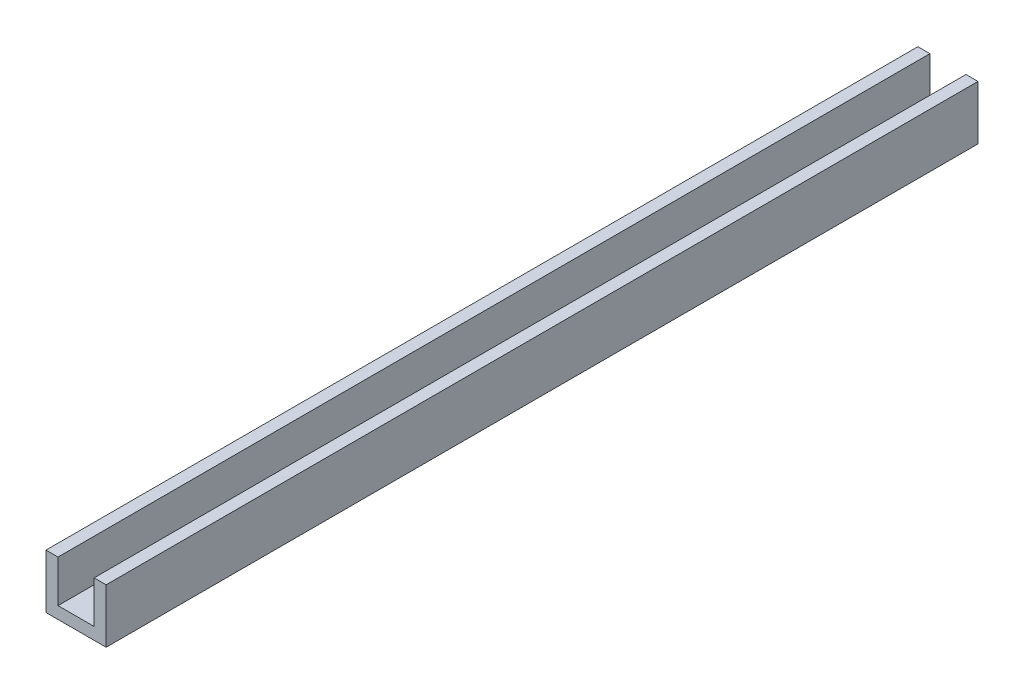
SolidWorks part; units mm, degrees
ref_plane "正面" through (0, 0, 0) normal (0, 0, 1) x (1, 0, 0)
ref_plane "平面" through (0, 0, 0) normal (0, 1, 0) x (1, 0, 0)
ref_plane "右側面" through (0, 0, 0) normal (1, 0, 0) x (0, 0, -1)
sketch "ｽｹｯﾁ1" plane through (0, 0, 0) normal (0, 0, 1) x (1, 0, 0)
  line L0 (-5, 9) -> (-5, 0)
  line L1 (-5, 0) -> (5, 0)
  line L2 (5, 0) -> (5, 9)
  line L3 (5, 9) -> (3, 9)
  line L4 (3, 9) -> (3, 2)
  line L5 (3, 2) -> (-3, 2)
  line L6 (-3, 2) -> (-3, 9)
  line L7 (-3, 9) -> (-5, 9)
  dimension "D1" = 9
  dimension "D2" = 9
  dimension "D3" = 10
  dimension "D4" = 5
  dimension "D5" = 2
  dimension "D6" = 2
  dimension "D7" = 2
extrude "ﾎﾞｽ - 押し出し1" add sketch "ｽｹｯﾁ1" along normal blind 245
sketch "ｽｹｯﾁ2" plane through (0, 0, 0) normal (0, -1, 0) x (1, 0, 0)
  line L0 (-5, 245) -> (5, 245) construction
  circle A0 centre (0, 225) radius 2.5
  circle A1 centre (0, 217) radius 2.5
  circle A2 centre (0, 122.5) radius 2.5
  circle A3 centre (0, 209) radius 2.5
  circle A4 centre (0, 193) radius 2.5
  circle A5 centre (0, 161) radius 2.5
  dimension "D1" = 20
  dimension "D3" = 5
  dimension "D4" = 5
  dimension "D5" = 5
  dimension "D6" = 122.5
  dimension "D7" = 5
  dimension "D8" = 8
  dimension "D9" = 5
  dimension "D10" = 16
  dimension "D11" = 5
  dimension "D12" = 32
  dimension "D2" = 28
extrude "ｶｯﾄ - 押し出し1" cut sketch "ｽｹｯﾁ2" against normal through all
ref_plane "平面1" through (0, 0, 122.5) normal (0, 0, 1) x (1, 0, 0)
mirror "ﾐﾗｰ1" about plane through (0, 0, 122.5) normal (0, 0, 1) of "ｶｯﾄ - 押し出し1"
sketch "ｽｹｯﾁ3" plane through (0, 0, 0) normal (0, -1, 0) x (1, 0, 0)
  line L0 (-5, 0) -> (-5, 100)
  line L1 (-5, 245) -> (-5, 0) construction
  line L2 (-5, 100) -> (5, 100)
  line L3 (5, 245) -> (5, 0) construction
  line L4 (5, 100) -> (5, 0)
  line L5 (5, 0) -> (-5, 0)
  dimension "D1" = 100
extrude "ｶｯﾄ - 押し出し2" cut sketch "ｽｹｯﾁ3" against normal through all both
